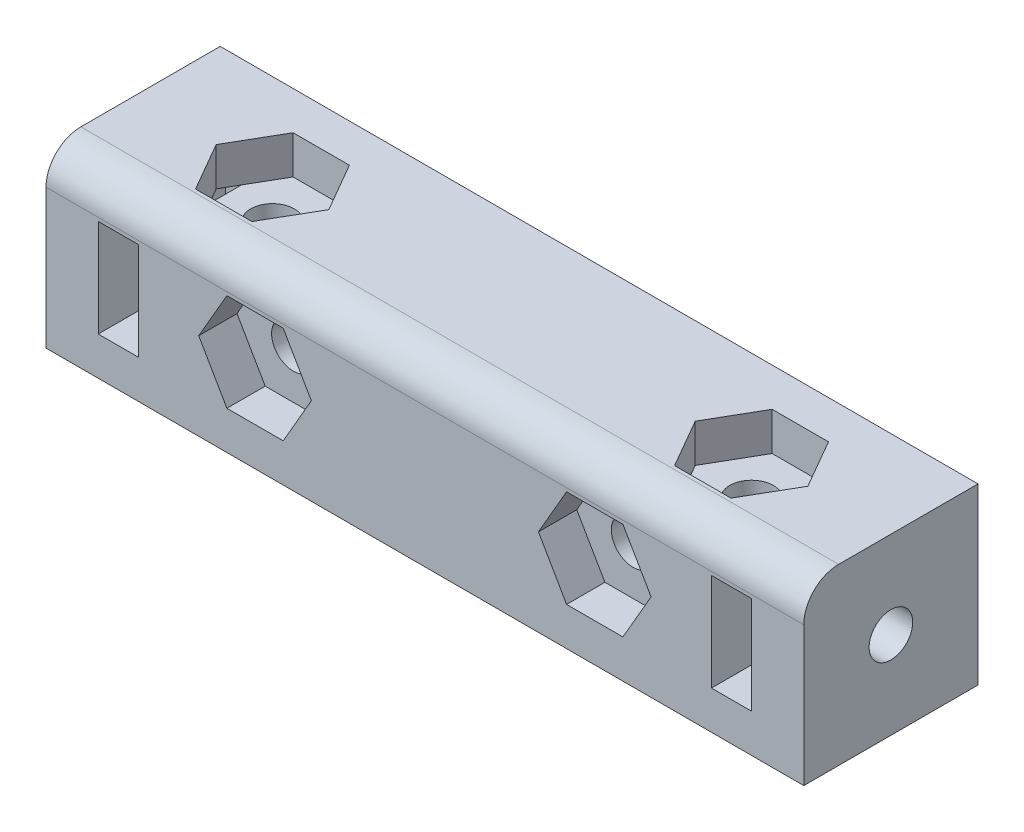
SolidWorks part; units mm, degrees
ref_plane "Front Plane" through (0, 0, 0) normal (0, 0, 1) x (1, 0, 0)
ref_plane "Top Plane" through (0, 0, 0) normal (0, 1, 0) x (1, 0, 0)
ref_plane "Right Plane" through (0, 0, 0) normal (1, 0, 0) x (0, 0, -1)
sketch "Sketch1" plane through (0, 0, 0) normal (0, 1, 0) x (1, 0, 0)
  line L1 (0, 0) -> (43.5, 0)
  line L2 (0, 0) -> (0, 10)
  line L3 (0, 10) -> (43.5, 10)
  line L4 (43.5, 0) -> (43.5, 10)
  dimension "D1" = 43.5
  dimension "D2" = 10
extrude "Boss-Extrude1" add sketch "Sketch1" along normal blind 10
sketch "Sketch2" plane through (0, 10, 0) normal (0, 1, 0) x (1, 0, 0)
  line L0 (0, 5) -> (43.5, 5) construction
  line L1 (0, 10) -> (0, 0) construction
  line L2 (43.5, 0) -> (43.5, 10) construction
  circle A0 centre (8, 5) radius 1.25
  circle A1 centre (35.5, 5) radius 1.25
  dimension "D3" = 2.5
  dimension "D4" = 2.5
  dimension "D1" = 8
  dimension "D2" = 8
extrude "Cut-Extrude1" cut sketch "Sketch2" against normal blind 10
sketch "Sketch3" plane through (0, 0, -10) normal (0, 0, -1) x (-1, 0, 0)
  line L0 (-43.5, 5) -> (0, 5) construction
  line L1 (-43.5, 10) -> (-43.5, 0) construction
  line L2 (0, 10) -> (0, 0) construction
  circle A0 centre (-31.5, 5) radius 1.25
  circle A1 centre (-12, 5) radius 1.25
  dimension "D1" = 2.5
  dimension "D2" = 2.5
  dimension "D3" = 12
  dimension "D4" = 12
extrude "Cut-Extrude2" cut sketch "Sketch3" against normal blind 10
sketch "Sketch4" plane through (43.5, 0, 0) normal (1, 0, 0) x (0, 0, -1)
  line L0 (5, 10) -> (5, 4.1725) construction
  line L1 (0, 10) -> (10, 10) construction
  line L2 (0, 5) -> (5.9702, 5) construction
  line L3 (0, 10) -> (0, 0) construction
  circle A0 centre (5, 5) radius 1.25
  dimension "D1" = 2.5
extrude "Cut-Extrude3" cut sketch "Sketch4" against normal blind 4
sketch "Sketch5" plane through (0, 0, 0) normal (-1, 0, 0) x (0, 0, 1)
  line L0 (-5, 10) -> (-5, 0) construction
  line L1 (-10, 10) -> (0, 10) construction
  line L2 (-10, 0) -> (0, 0) construction
  line L3 (-10, 5) -> (0, 5) construction
  line L4 (-10, 10) -> (-10, 0) construction
  line L5 (0, 10) -> (0, 0) construction
  circle A0 centre (-5, 5) radius 1.25
  dimension "D1" = 2.5
extrude "Cut-Extrude4" cut sketch "Sketch5" against normal blind 4
sketch "Sketch6" plane through (0, 10, 0) normal (0, 1, 0) x (1, 0, 0)
  line L0 (43.5, 10) -> (0, 10) construction
  line L1 (9.6166, 2.2) -> (11.2332, 5)
  line L2 (11.2332, 5) -> (9.6166, 7.8)
  line L3 (9.6166, 7.8) -> (6.3834, 7.8)
  line L4 (6.3834, 7.8) -> (4.7668, 5)
  line L5 (4.7668, 5) -> (6.3834, 2.2)
  line L6 (6.3834, 2.2) -> (9.6166, 2.2)
  circle A0 centre (8, 5) radius 2.8 construction
  dimension "D1" = 5.6
extrude "Cut-Extrude5" cut sketch "Sketch6" against normal blind 2.2
sketch "Sketch7" plane through (0, 10, 0) normal (0, 1, 0) x (1, 0, 0)
  line L0 (43.5, 10) -> (0, 10) construction
  line L1 (33.8834, 7.8) -> (32.2668, 5)
  line L2 (32.2668, 5) -> (33.8834, 2.2)
  line L3 (33.8834, 2.2) -> (37.1166, 2.2)
  line L4 (37.1166, 2.2) -> (38.7332, 5)
  line L5 (38.7332, 5) -> (37.1166, 7.8)
  line L6 (37.1166, 7.8) -> (33.8834, 7.8)
  circle A0 centre (35.5, 5) radius 2.8 construction
  dimension "D1" = 5.6
extrude "Cut-Extrude6" cut sketch "Sketch7" against normal blind 2.2
sketch "Sketch8" plane through (0, 0, 0) normal (0, 0, 1) x (1, 0, 0)
  line L0 (0, 10) -> (43.5, 10) construction
  line L1 (10.3834, 2.2) -> (13.6166, 2.2)
  line L2 (13.6166, 2.2) -> (15.2332, 5)
  line L3 (15.2332, 5) -> (13.6166, 7.8)
  line L4 (13.6166, 7.8) -> (10.3834, 7.8)
  line L5 (10.3834, 7.8) -> (8.7668, 5)
  line L6 (8.7668, 5) -> (10.3834, 2.2)
  circle A0 centre (12, 5) radius 2.8 construction
  dimension "D1" = 5.6
extrude "Cut-Extrude7" cut sketch "Sketch8" against normal blind 2.2
sketch "Sketch9" plane through (0, 0, 0) normal (0, 0, 1) x (1, 0, 0)
  line L1 (33.1166, 7.8) -> (29.8834, 7.8)
  line L2 (29.8834, 7.8) -> (28.2668, 5)
  line L3 (28.2668, 5) -> (29.8834, 2.2)
  line L4 (29.8834, 2.2) -> (33.1166, 2.2)
  line L5 (33.1166, 2.2) -> (34.7332, 5)
  line L6 (34.7332, 5) -> (33.1166, 7.8)
  circle A0 centre (31.5, 5) radius 2.8 construction
  dimension "D1" = 5.6
extrude "Cut-Extrude8" cut sketch "Sketch9" against normal blind 2.2
sketch "Sketch11" plane through (0, 0, 0) normal (0, 0, 1) x (1, 0, 0)
  line L0 (0, 5) -> (43.5, 5) construction
  line L1 (0, 10) -> (0, 0) construction
  line L2 (43.5, 10) -> (43.5, 0) construction
  line L4 (3, 2.2) -> (5.3, 2.2)
  line L5 (3, 2.2) -> (3, 7.8)
  line L6 (3, 7.8) -> (5.3, 7.8)
  line L7 (5.3, 2.2) -> (5.3, 7.8)
  line L8 (3, 2.2) -> (5.3, 7.8) construction
  line L9 (3, 7.8) -> (5.3, 2.2) construction
  line L10 (38.2, 2.2) -> (40.5, 2.2)
  line L11 (38.2, 2.2) -> (38.2, 7.8)
  line L12 (38.2, 7.8) -> (40.5, 7.8)
  line L13 (40.5, 2.2) -> (40.5, 7.8)
  line L14 (38.2, 2.2) -> (40.5, 7.8) construction
  line L15 (38.2, 7.8) -> (40.5, 2.2) construction
  point P6 (4.15, 5)
  point P11 (39.35, 5)
  dimension "D1" = 2.3
  dimension "D2" = 5.6
  dimension "D3" = 2.3
  dimension "D4" = 5.6
  dimension "D5" = 3
  dimension "D6" = 3
extrude "Cut-Extrude9" cut sketch "Sketch11" against normal blind 7.3
fillet "Fillet1" radius 2 1 edges at (21.75, 10, 0)
